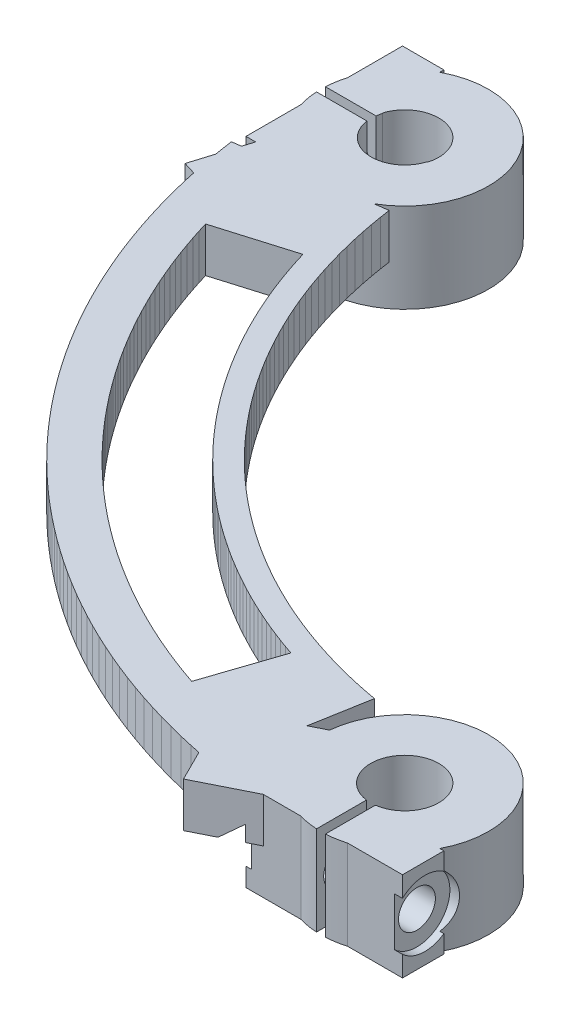
SolidWorks part; units mm, degrees
other "Suspension Travel Stop Plate"
other "Suspension Travel Stop Plate Left"
ref_plane "Front Plane" through (0, 0, 0) normal (0, 0, 1) x (1, 0, 0)
ref_plane "Top Plane" through (0, 0, 0) normal (0, 1, 0) x (1, 0, 0)
ref_plane "Right Plane" through (0, 0, 0) normal (1, 0, 0) x (0, 0, -1)
sketch3d "Main Profile Sketch datum points"
  point P0 (0, -120, 0)
  point P1 (10, -120, 0)
  point P2 (0, -120, 10)
ref_plane "Main Profile Sketch plane" through (0, -120, 0) normal (0, -1, 0) x (-1, 0, 0)
sketch "Main Profile Sketch" plane through (0, -120, 0) normal (0, -1, 0) x (-1, 0, 0)
  line L0 (49.2917, -53.5) -> (49.2917, -57.2)
  line L1 (49.2917, -57.2) -> (54.1917, -57.2)
  line L2 (55.8917, -53.0237) -> (55.8917, -57.4893)
  line L3 (56.6917, -53.0237) -> (56.6917, -57.4893)
  line L4 (58.3917, -57.2) -> (61.7474, -57.2)
  line L5 (61.7474, -57.2) -> (66.5028, -59.5777)
  line L6 (66.5028, -59.5777) -> (67.8774, -56.8285)
  line L7 (68.7463, -56.647) -> (67.8774, -56.8285)
  line L8 (69.9299, -56.3737) -> (68.7463, -56.647)
  line L9 (71.1075, -56.0758) -> (69.9299, -56.3737)
  line L10 (72.2786, -55.7532) -> (71.1075, -56.0758)
  line L11 (73.4427, -55.4061) -> (72.2786, -55.7532)
  line L12 (74.5993, -55.0348) -> (73.4427, -55.4061)
  line L13 (75.7478, -54.6393) -> (74.5993, -55.0348)
  line L14 (76.8879, -54.2199) -> (75.7478, -54.6393)
  line L15 (78.0188, -53.7767) -> (76.8879, -54.2199)
  line L16 (79.1403, -53.3098) -> (78.0188, -53.7767)
  line L17 (80.2517, -52.8197) -> (79.1403, -53.3098)
  line L18 (81.3526, -52.3063) -> (80.2517, -52.8197)
  line L19 (82.4425, -51.77) -> (81.3526, -52.3063)
  line L20 (83.521, -51.211) -> (82.4425, -51.77)
  line L21 (84.5875, -50.6295) -> (83.521, -51.211)
  line L22 (85.6416, -50.0258) -> (84.5875, -50.6295)
  line L23 (86.6828, -49.4002) -> (85.6416, -50.0258)
  line L24 (87.7107, -48.7529) -> (86.6828, -49.4002)
  line L25 (88.7248, -48.0842) -> (87.7107, -48.7529)
  line L26 (89.7247, -47.3944) -> (88.7248, -48.0842)
  line L27 (90.7099, -46.6838) -> (89.7247, -47.3944)
  line L28 (91.6801, -45.9528) -> (90.7099, -46.6838)
  line L29 (92.6347, -45.2016) -> (91.6801, -45.9528)
  line L30 (93.5733, -44.4306) -> (92.6347, -45.2016)
  line L31 (94.4956, -43.6401) -> (93.5733, -44.4306)
  line L32 (95.4012, -42.8304) -> (94.4956, -43.6401)
  line L33 (96.2896, -42.002) -> (95.4012, -42.8304)
  line L34 (97.1604, -41.1551) -> (96.2896, -42.002)
  line L35 (98.0134, -40.2902) -> (97.1604, -41.1551)
  line L36 (98.848, -39.4076) -> (98.0134, -40.2902)
  line L37 (99.6639, -38.5077) -> (98.848, -39.4076)
  line L38 (100.4609, -37.591) -> (99.6639, -38.5077)
  line L39 (101.2384, -36.6577) -> (100.4609, -37.591)
  line L40 (101.9963, -35.7084) -> (101.2384, -36.6577)
  line L41 (102.7341, -34.7434) -> (101.9963, -35.7084)
  line L42 (103.4515, -33.7631) -> (102.7341, -34.7434)
  line L43 (104.1482, -32.7681) -> (103.4515, -33.7631)
  line L44 (104.824, -31.7587) -> (104.1482, -32.7681)
  line L45 (105.4784, -30.7353) -> (104.824, -31.7587)
  line L46 (106.1113, -29.6985) -> (105.4784, -30.7353)
  line L47 (106.7224, -28.6486) -> (106.1113, -29.6985)
  line L48 (107.3113, -27.5862) -> (106.7224, -28.6486)
  line L49 (107.8778, -26.5117) -> (107.3113, -27.5862)
  line L50 (108.4217, -25.4255) -> (107.8778, -26.5117)
  line L51 (108.9427, -24.3282) -> (108.4217, -25.4255)
  line L52 (109.4407, -23.2202) -> (108.9427, -24.3282)
  line L53 (109.9153, -22.1021) -> (109.4407, -23.2202)
  line L54 (110.3664, -20.9742) -> (109.9153, -22.1021)
  line L55 (110.7938, -19.8372) -> (110.3664, -20.9742)
  line L56 (111.1973, -18.6914) -> (110.7938, -19.8372)
  line L57 (111.5767, -17.5375) -> (111.1973, -18.6914)
  line L58 (111.9319, -16.3758) -> (111.5767, -17.5375)
  line L59 (112.2626, -15.207) -> (111.9319, -16.3758)
  line L60 (112.5688, -14.0315) -> (112.2626, -15.207)
  line L61 (112.8503, -12.8498) -> (112.5688, -14.0315)
  line L62 (112.9979, -12.1673) -> (112.8503, -12.8498)
  line L63 (112.9979, -12.1673) -> (114.1148, -11.8237)
  line L64 (114.1148, -11.8237) -> (113.468, -9.7218)
  line L65 (113.5456, -9.2731) -> (113.468, -9.7218)
  line L66 (113.7272, -8.072) -> (113.5456, -9.2731)
  line L67 (112.9258, -7.9594) -> (113.7272, -8.072)
  line L68 (112.9258, -7.9594) -> (112.6306, -7)
  line L69 (112.6306, -7) -> (113.4917, -7)
  line L70 (113.4917, -2.1) -> (113.4917, -7)
  line L71 (109.2649, -0.4) -> (113.781, -0.4)
  line L72 (103.4243, -0.8823) -> (103.3765, -0.897)
  line L73 (109.2068, 0.897) -> (109.159, 0.8823)
  line L74 (109.2649, 0.4) -> (113.781, 0.4)
  line L75 (113.4917, 7) -> (113.4917, 2.1)
  line L76 (109.7917, 7) -> (113.4917, 7)
  line L77 (109.7917, 7) -> (109.7917, 6.6332)
  line L78 (101.3488, -6.3324) -> (102.5527, -6.5016)
  line L79 (101.2064, -7.2746) -> (101.3488, -6.3324)
  line L80 (101.0442, -8.2136) -> (101.2064, -7.2746)
  line L81 (100.8623, -9.149) -> (101.0442, -8.2136)
  line L82 (100.6609, -10.0805) -> (100.8623, -9.149)
  line L83 (100.4401, -11.0074) -> (100.6609, -10.0805)
  line L84 (100.1999, -11.9296) -> (100.4401, -11.0074)
  line L85 (99.9404, -12.8465) -> (100.1999, -11.9296)
  line L86 (99.6618, -13.7578) -> (99.9404, -12.8465)
  line L87 (99.3642, -14.6631) -> (99.6618, -13.7578)
  line L88 (99.0477, -15.5619) -> (99.3642, -14.6631)
  line L89 (98.7124, -16.4539) -> (99.0477, -15.5619)
  line L90 (98.3585, -17.3387) -> (98.7124, -16.4539)
  line L91 (97.9862, -18.2159) -> (98.3585, -17.3387)
  line L92 (97.5955, -19.0851) -> (97.9862, -18.2159)
  line L93 (97.1868, -19.9459) -> (97.5955, -19.0851)
  line L94 (96.7601, -20.798) -> (97.1868, -19.9459)
  line L95 (96.3157, -21.6409) -> (96.7601, -20.798)
  line L96 (95.8537, -22.4744) -> (96.3157, -21.6409)
  line L97 (95.3743, -23.298) -> (95.8537, -22.4744)
  line L98 (94.8778, -24.1113) -> (95.3743, -23.298)
  line L99 (94.3644, -24.9141) -> (94.8778, -24.1113)
  line L100 (93.8343, -25.706) -> (94.3644, -24.9141)
  line L101 (93.2877, -26.4866) -> (93.8343, -25.706)
  line L102 (92.7249, -27.2556) -> (93.2877, -26.4866)
  line L103 (92.1461, -28.0126) -> (92.7249, -27.2556)
  line L104 (91.5516, -28.7573) -> (92.1461, -28.0126)
  line L105 (90.9416, -29.4895) -> (91.5516, -28.7573)
  line L106 (90.3165, -30.2086) -> (90.9416, -29.4895)
  line L107 (89.6764, -30.9146) -> (90.3165, -30.2086)
  line L108 (89.0216, -31.607) -> (89.6764, -30.9146)
  line L109 (88.3525, -32.2855) -> (89.0216, -31.607)
  line L110 (87.6693, -32.9498) -> (88.3525, -32.2855)
  line L111 (86.9724, -33.5997) -> (87.6693, -32.9498)
  line L112 (86.262, -34.2349) -> (86.9724, -33.5997)
  line L113 (85.5385, -34.855) -> (86.262, -34.2349)
  line L114 (84.8021, -35.4599) -> (85.5385, -34.855)
  line L115 (84.0533, -36.0492) -> (84.8021, -35.4599)
  line L116 (83.2922, -36.6227) -> (84.0533, -36.0492)
  line L117 (82.5193, -37.1801) -> (83.2922, -36.6227)
  line L118 (81.7349, -37.7212) -> (82.5193, -37.1801)
  line L119 (80.9394, -38.2458) -> (81.7349, -37.7212)
  line L120 (80.133, -38.7536) -> (80.9394, -38.2458)
  line L121 (79.3162, -39.2444) -> (80.133, -38.7536)
  line L122 (78.4893, -39.718) -> (79.3162, -39.2444)
  line L123 (77.6526, -40.1741) -> (78.4893, -39.718)
  line L124 (76.8066, -40.6127) -> (77.6526, -40.1741)
  line L125 (75.9516, -41.0334) -> (76.8066, -40.6127)
  line L126 (75.0879, -41.4361) -> (75.9516, -41.0334)
  line L127 (74.216, -41.8207) -> (75.0879, -41.4361)
  line L128 (73.3363, -42.1869) -> (74.216, -41.8207)
  line L129 (72.449, -42.5346) -> (73.3363, -42.1869)
  line L130 (71.5547, -42.8636) -> (72.449, -42.5346)
  line L131 (70.6537, -43.1739) -> (71.5547, -42.8636)
  line L132 (69.7464, -43.4652) -> (70.6537, -43.1739)
  line L133 (68.8332, -43.7374) -> (69.7464, -43.4652)
  line L134 (67.9144, -43.9905) -> (68.8332, -43.7374)
  line L135 (66.9906, -44.2242) -> (67.9144, -43.9905)
  line L136 (66.0621, -44.4386) -> (66.9906, -44.2242)
  line L137 (65.1293, -44.6335) -> (66.0621, -44.4386)
  line L138 (64.1926, -44.8088) -> (65.1293, -44.6335)
  line L139 (65.0956, -49.9299) -> (64.1926, -44.8088)
  line L140 (65.0956, -49.9299) -> (63.755, -49.2595)
  line L141 (49.2917, -53.5) -> (49.6584, -53.5)
  line L142 (100.8479, -16.4618) -> (101.1044, -15.7502)
  line L143 (101.1044, -15.7502) -> (101.3495, -15.0346)
  line L144 (101.3495, -15.0346) -> (101.5832, -14.3152)
  line L145 (101.5832, -14.3152) -> (101.8054, -13.5922)
  line L146 (101.8054, -13.5922) -> (108.5127, -15.5953)
  line L147 (108.5127, -15.5953) -> (108.2577, -16.4249)
  line L148 (108.2577, -16.4249) -> (107.9896, -17.2503)
  line L149 (107.9896, -17.2503) -> (107.7084, -18.0713)
  line L150 (107.7084, -18.0713) -> (107.4141, -18.8878)
  line L151 (107.4141, -18.8878) -> (107.1068, -19.6995)
  line L152 (107.1068, -19.6995) -> (106.7867, -20.5061)
  line L153 (106.7867, -20.5061) -> (106.4537, -21.3076)
  line L154 (106.4537, -21.3076) -> (106.1081, -22.1037)
  line L155 (106.1081, -22.1037) -> (105.7498, -22.8942)
  line L156 (105.7498, -22.8942) -> (105.379, -23.6788)
  line L157 (105.379, -23.6788) -> (104.9957, -24.4575)
  line L158 (104.9957, -24.4575) -> (104.6, -25.2299)
  line L159 (104.6, -25.2299) -> (104.1922, -25.996)
  line L160 (104.1922, -25.996) -> (103.7721, -26.7555)
  line L161 (103.7721, -26.7555) -> (103.3401, -27.5081)
  line L162 (103.3401, -27.5081) -> (102.8961, -28.2538)
  line L163 (102.8961, -28.2538) -> (102.4402, -28.9924)
  line L164 (102.4402, -28.9924) -> (101.9727, -29.7236)
  line L165 (101.9727, -29.7236) -> (101.4936, -30.4472)
  line L166 (101.4936, -30.4472) -> (101.003, -31.1631)
  line L167 (101.003, -31.1631) -> (100.5011, -31.8712)
  line L168 (100.5011, -31.8712) -> (99.988, -32.5711)
  line L169 (99.988, -32.5711) -> (99.4638, -33.2628)
  line L170 (99.4638, -33.2628) -> (98.9287, -33.9461)
  line L171 (98.9287, -33.9461) -> (98.3827, -34.6207)
  line L172 (98.3827, -34.6207) -> (97.8261, -35.2866)
  line L173 (97.8261, -35.2866) -> (97.2589, -35.9435)
  line L174 (97.2589, -35.9435) -> (96.6814, -36.5913)
  line L175 (96.6814, -36.5913) -> (96.0936, -37.2298)
  line L176 (96.0936, -37.2298) -> (95.4957, -37.8589)
  line L177 (95.4957, -37.8589) -> (94.8878, -38.4784)
  line L178 (94.8878, -38.4784) -> (94.2702, -39.0881)
  line L179 (94.2702, -39.0881) -> (93.643, -39.6879)
  line L180 (93.643, -39.6879) -> (93.0063, -40.2776)
  line L181 (93.0063, -40.2776) -> (92.3602, -40.8572)
  line L182 (92.3602, -40.8572) -> (91.705, -41.4263)
  line L183 (91.705, -41.4263) -> (91.0409, -41.985)
  line L184 (91.0409, -41.985) -> (90.3679, -42.533)
  line L185 (90.3679, -42.533) -> (89.6863, -43.0703)
  line L186 (89.6863, -43.0703) -> (88.9962, -43.5966)
  line L187 (88.9962, -43.5966) -> (88.2978, -44.1118)
  line L188 (88.2978, -44.1118) -> (87.5914, -44.6159)
  line L189 (87.5914, -44.6159) -> (86.8769, -45.1087)
  line L190 (86.8769, -45.1087) -> (86.1547, -45.59)
  line L191 (86.1547, -45.59) -> (85.425, -46.0597)
  line L192 (85.425, -46.0597) -> (84.6879, -46.5178)
  line L193 (84.6879, -46.5178) -> (83.9435, -46.9641)
  line L194 (83.9435, -46.9641) -> (83.1922, -47.3985)
  line L195 (83.1922, -47.3985) -> (82.434, -47.8208)
  line L196 (82.434, -47.8208) -> (81.6692, -48.231)
  line L197 (81.6692, -48.231) -> (80.8979, -48.629)
  line L198 (80.8979, -48.629) -> (80.1204, -49.0147)
  line L199 (80.1204, -49.0147) -> (79.3369, -49.3879)
  line L200 (79.3369, -49.3879) -> (78.5475, -49.7486)
  line L201 (78.5475, -49.7486) -> (77.7525, -50.0967)
  line L202 (77.7525, -50.0967) -> (76.9521, -50.4321)
  line L203 (76.9521, -50.4321) -> (76.1464, -50.7547)
  line L204 (76.1464, -50.7547) -> (75.3357, -51.0644)
  line L205 (75.3357, -51.0644) -> (74.5201, -51.3612)
  line L206 (74.5201, -51.3612) -> (73.6999, -51.645)
  line L207 (73.6999, -51.645) -> (71.464, -45.0117)
  line L208 (71.464, -45.0117) -> (72.1788, -44.7644)
  line L209 (72.1788, -44.7644) -> (72.8896, -44.5057)
  line L210 (72.8896, -44.5057) -> (73.5962, -44.2357)
  line L211 (73.5962, -44.2357) -> (74.2984, -43.9546)
  line L212 (74.2984, -43.9546) -> (74.9961, -43.6623)
  line L213 (74.9961, -43.6623) -> (75.689, -43.3589)
  line L214 (75.689, -43.3589) -> (76.377, -43.0445)
  line L215 (76.377, -43.0445) -> (77.0599, -42.7192)
  line L216 (77.0599, -42.7192) -> (77.7375, -42.3831)
  line L217 (77.7375, -42.3831) -> (78.4097, -42.0362)
  line L218 (78.4097, -42.0362) -> (79.0762, -41.6787)
  line L219 (79.0762, -41.6787) -> (79.737, -41.3106)
  line L220 (79.737, -41.3106) -> (80.3919, -40.932)
  line L221 (80.3919, -40.932) -> (81.0406, -40.543)
  line L222 (81.0406, -40.543) -> (81.6831, -40.1438)
  line L223 (81.6831, -40.1438) -> (82.3191, -39.7344)
  line L224 (82.3191, -39.7344) -> (82.9485, -39.3149)
  line L225 (82.9485, -39.3149) -> (83.5712, -38.8854)
  line L226 (83.5712, -38.8854) -> (84.187, -38.4461)
  line L227 (84.187, -38.4461) -> (84.7956, -37.997)
  line L228 (84.7956, -37.997) -> (85.3971, -37.5383)
  line L229 (85.3971, -37.5383) -> (85.9911, -37.0701)
  line L230 (85.9911, -37.0701) -> (86.5777, -36.5924)
  line L231 (86.5777, -36.5924) -> (87.1565, -36.1055)
  line L232 (87.1565, -36.1055) -> (87.7276, -35.6095)
  line L233 (87.7276, -35.6095) -> (88.2906, -35.1044)
  line L234 (88.2906, -35.1044) -> (88.8456, -34.5904)
  line L235 (88.8456, -34.5904) -> (89.3922, -34.0676)
  line L236 (89.3922, -34.0676) -> (89.9305, -33.5362)
  line L237 (89.9305, -33.5362) -> (90.4603, -32.9963)
  line L238 (90.4603, -32.9963) -> (90.9814, -32.448)
  line L239 (90.9814, -32.448) -> (91.4937, -31.8915)
  line L240 (91.4937, -31.8915) -> (91.9971, -31.3269)
  line L241 (91.9971, -31.3269) -> (92.4914, -30.7543)
  line L242 (92.4914, -30.7543) -> (92.9765, -30.174)
  line L243 (92.9765, -30.174) -> (93.4524, -29.586)
  line L244 (93.4524, -29.586) -> (93.9188, -28.9905)
  line L245 (93.9188, -28.9905) -> (94.3756, -28.3877)
  line L246 (94.3756, -28.3877) -> (94.8228, -27.7776)
  line L247 (94.8228, -27.7776) -> (95.2603, -27.1605)
  line L248 (95.2603, -27.1605) -> (95.6879, -26.5366)
  line L249 (95.6879, -26.5366) -> (96.1054, -25.9059)
  line L250 (96.1054, -25.9059) -> (96.5129, -25.2686)
  line L251 (96.5129, -25.2686) -> (96.9102, -24.6249)
  line L252 (96.9102, -24.6249) -> (97.2971, -23.975)
  line L253 (97.2971, -23.975) -> (97.6737, -23.319)
  line L254 (97.6737, -23.319) -> (98.0398, -22.6571)
  line L255 (98.0398, -22.6571) -> (98.3953, -21.9894)
  line L256 (98.3953, -21.9894) -> (98.7401, -21.3161)
  line L257 (98.7401, -21.3161) -> (99.0742, -20.6375)
  line L258 (99.0742, -20.6375) -> (99.3974, -19.9536)
  line L259 (99.3974, -19.9536) -> (99.7096, -19.2647)
  line L260 (99.7096, -19.2647) -> (100.0109, -18.5709)
  line L261 (100.0109, -18.5709) -> (100.3011, -17.8723)
  line L262 (100.3011, -17.8723) -> (100.5801, -17.1693)
  line L263 (100.5801, -17.1693) -> (100.8479, -16.4618)
  arc A0 (54.1917, -57.2) -> (55.8917, -57.4893) centre (56.2917, -50) ccw
  arc A1 (56.2917, -46.95) -> (55.8917, -53.0237) centre (56.2917, -50) ccw
  arc A2 (56.6917, -53.0237) -> (56.2917, -46.95) centre (56.2917, -50) ccw
  arc A3 (56.6917, -57.4893) -> (58.3917, -57.2) centre (56.2917, -50) ccw
  arc A4 (113.4917, -2.1) -> (113.781, -0.4) centre (106.2917, 0) ccw
  arc A5 (103.4243, -0.8823) -> (109.2649, -0.4) centre (106.2917, 0) ccw
  arc A6 (109.2068, 0.897) -> (103.3765, -0.897) centre (106.2917, 0) ccw
  arc A7 (109.2649, 0.4) -> (109.159, 0.8823) centre (106.2917, 0) ccw
  arc A8 (113.781, 0.4) -> (113.4917, 2.1) centre (106.2917, 0) ccw
  arc A9 (109.7917, 6.6332) -> (102.5527, -6.5016) centre (106.2917, 0) ccw
  arc A10 (63.755, -49.2595) -> (49.6584, -53.5) centre (56.2917, -50) ccw
extrude "Main Extrusion" add sketch "Main Profile Sketch" against normal blind 4 separate body
sketch3d "Detail Profile 2 Sketch datum points"
  point P0 (0, -116, 0)
  point P1 (10, -116, 0)
  point P2 (0, -116, 10)
ref_plane "Detail Profile 2 Sketch plane" through (0, -116, 0) normal (0, -1, 0) x (-1, 0, 0)
sketch "Detail Profile 2 Sketch" plane through (0, -116, 0) normal (0, -1, 0) x (-1, 0, 0)
  line L0 (49.2917, -53.5) -> (49.2917, -57.2)
  line L1 (49.2917, -57.2) -> (54.1917, -57.2)
  line L2 (55.8917, -53.0237) -> (55.8917, -57.4893)
  line L3 (56.6917, -53.0237) -> (56.6917, -57.4893)
  line L4 (58.3917, -57.2) -> (63.2917, -57.2)
  line L5 (63.2917, -53.5) -> (63.2917, -57.2)
  line L6 (62.9249, -53.5) -> (63.2917, -53.5)
  line L7 (49.2917, -53.5) -> (49.6584, -53.5)
  line L8 (109.7917, -7) -> (113.4917, -7)
  line L9 (113.4917, -2.1) -> (113.4917, -7)
  line L10 (109.3153, -0.4) -> (113.781, -0.4)
  line L11 (109.3153, 0.4) -> (113.781, 0.4)
  line L12 (113.4917, 7) -> (113.4917, 2.1)
  line L13 (109.7917, 7) -> (113.4917, 7)
  line L14 (109.7917, 7) -> (109.7917, 6.6332)
  line L15 (109.7917, -6.6332) -> (109.7917, -7)
  arc A0 (54.1917, -57.2) -> (55.8917, -57.4893) centre (56.2917, -50) ccw
  arc A1 (56.2917, -46.95) -> (55.8917, -53.0237) centre (56.2917, -50) ccw
  arc A2 (56.6917, -53.0237) -> (56.2917, -46.95) centre (56.2917, -50) ccw
  arc A3 (56.6917, -57.4893) -> (58.3917, -57.2) centre (56.2917, -50) ccw
  arc A4 (62.9249, -53.5) -> (49.6584, -53.5) centre (56.2917, -50) ccw
  arc A5 (113.4917, -2.1) -> (113.781, -0.4) centre (106.2917, 0) ccw
  arc A6 (109.3153, 0.4) -> (109.3153, -0.4) centre (106.2917, 0) ccw
  arc A7 (113.781, 0.4) -> (113.4917, 2.1) centre (106.2917, 0) ccw
  arc A8 (109.7917, 6.6332) -> (109.7917, -6.6332) centre (106.2917, 0) ccw
extrude "Detail Extrusion 2" add sketch "Detail Profile 2 Sketch" against normal blind 4
sketch3d "Stop Clamp Bore 1 profile datum points"
  point P0 (-111.4917, -116, -10)
  point P1 (-101.4917, -116, -10)
  point P2 (-111.4917, -106, -10)
ref_plane "Stop Clamp Bore 1 profile plane" through (0, 0, -10) normal (0, 0, 1) x (1, 0, 0)
sketch "Stop Clamp Bore 1 profile" plane through (0, 0, -10) normal (0, 0, 1) x (1, 0, 0)
  circle A0 centre (-111.4917, -116) radius 1.65
extrude "Stop Clamp Bore 1" cut sketch "Stop Clamp Bore 1 profile" along normal blind 20
sketch3d "Stop Clamp Bore 2 profile datum points"
  point P0 (-66.2917, -116, 55.2)
  point P1 (-66.2917, -106, 55.2)
  point P2 (-66.2917, -116, 65.2)
ref_plane "Stop Clamp Bore 2 profile plane" through (-66.2917, 0, 0) normal (1, 0, 0) x (0, 0, -1)
sketch "Stop Clamp Bore 2 profile" plane through (-66.2917, 0, 0) normal (1, 0, 0) x (0, 0, -1)
  circle A0 centre (-55.2, -116) radius 1.65
extrude "Stop Clamp Bore 2" cut sketch "Stop Clamp Bore 2 profile" along normal blind 20
sketch3d "Stop Clamp Bore 3 profile datum points"
  point P0 (-111.4917, -116, -11)
  point P1 (-101.4917, -116, -11)
  point P2 (-111.4917, -106, -11)
ref_plane "Stop Clamp Bore 3 profile plane" through (0, 0, -11) normal (0, 0, 1) x (1, 0, 0)
sketch "Stop Clamp Bore 3 profile" plane through (0, 0, -11) normal (0, 0, 1) x (1, 0, 0)
  circle A0 centre (-111.4917, -116) radius 1.6
extrude "Stop Clamp Bore 3" cut sketch "Stop Clamp Bore 3 profile" along normal blind 40
sketch3d "Stop Clamp Bore 4 profile datum points"
  point P0 (-111.4917, -116, 20)
  point P1 (-101.4917, -116, 20)
  point P2 (-111.4917, -106, 20)
ref_plane "Stop Clamp Bore 4 profile plane" through (0, 0, 20) normal (0, 0, 1) x (1, 0, 0)
sketch "Stop Clamp Bore 4 profile" plane through (0, 0, 20) normal (0, 0, 1) x (1, 0, 0)
  circle A0 centre (-111.4917, -116) radius 2.9
extrude "Stop Clamp Bore 4" cut sketch "Stop Clamp Bore 4 profile" along normal blind 15
sketch3d "Stop Clamp Bore 5 profile datum points"
  point P0 (-67, -116, 55.2)
  point P1 (-67, -106, 55.2)
  point P2 (-67, -116, 65.2)
ref_plane "Stop Clamp Bore 5 profile plane" through (-67, 0, 0) normal (1, 0, 0) x (0, 0, -1)
sketch "Stop Clamp Bore 5 profile" plane through (-67, 0, 0) normal (1, 0, 0) x (0, 0, -1)
  circle A0 centre (-55.2, -116) radius 1.6
extrude "Stop Clamp Bore 5" cut sketch "Stop Clamp Bore 5 profile" along normal blind 23
sketch3d "Stop Clamp Bore 6 profile datum points"
  point P0 (-50, -116, 55.2)
  point P1 (-50, -106, 55.2)
  point P2 (-50, -116, 65.2)
ref_plane "Stop Clamp Bore 6 profile plane" through (-50, 0, 0) normal (1, 0, 0) x (0, 0, -1)
sketch "Stop Clamp Bore 6 profile" plane through (-50, 0, 0) normal (1, 0, 0) x (0, 0, -1)
  circle A0 centre (-55.2, -116) radius 2.95
extrude "Stop Clamp Bore 6" cut sketch "Stop Clamp Bore 6 profile" along normal blind 6
sketch3d "Captured Nut Sketch datum points"
  point P0 (-66, -116, 55.2)
  point P1 (-66, -106, 55.2)
  point P2 (-66, -116, 65.2)
ref_plane "Captured Nut Sketch plane" through (-66, 0, 0) normal (1, 0, 0) x (0, 0, -1)
sketch "Captured Nut Sketch" plane through (-66, 0, 0) normal (1, 0, 0) x (0, 0, -1)
  line L0 (-56.8743, -113.1) -> (-58.5486, -116)
  line L1 (-58.5486, -116) -> (-56.8743, -118.9)
  line L2 (-56.8743, -118.9) -> (-53.5257, -118.9)
  line L3 (-53.5257, -118.9) -> (-51.8514, -116)
  line L4 (-51.8514, -116) -> (-53.5257, -113.1)
  line L5 (-53.5257, -113.1) -> (-56.8743, -113.1)
extrude "Captured Nut Pocket" cut sketch "Captured Nut Sketch" along normal blind 3.2
sketch3d "Mirror1 profile datum points"
  point P0 (0, 0, 0)
  point P1 (10, 0, 0)
  point P2 (0, 0, 10)
ref_plane "Mirror1 profile plane" through (0, 0, 0) normal (0, -1, 0) x (-1, 0, 0)
mirror "Mirror1" about plane through (0, 0, 0) normal (0, -1, 0) of bodies 109
delete or keep bodies "Remove1" type delete bodies bodies 109
